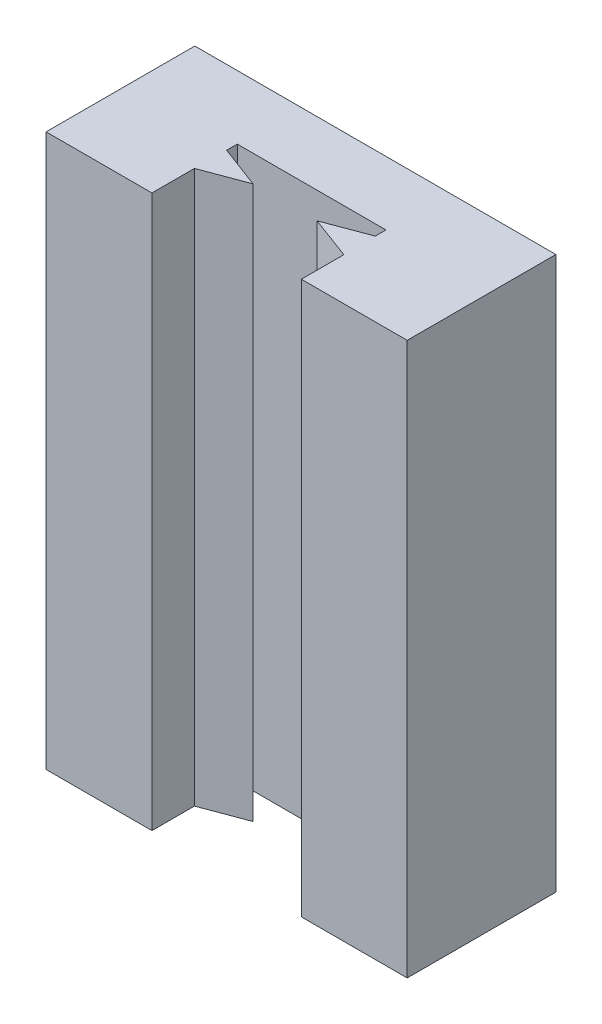
SolidWorks part; units mm, degrees
ref_plane "前视基准面" through (0, 0, 0) normal (0, 0, 1) x (1, 0, 0)
ref_plane "上视基准面" through (0, 0, 0) normal (0, 1, 0) x (1, 0, 0)
ref_plane "右视基准面" through (0, 0, 0) normal (1, 0, 0) x (0, 0, -1)
sketch "草图1" plane through (0, 0, 0) normal (0, 1, 0) x (1, 0, 0)
  line L0 (-96.3317, 0) -> (111.273, 0) construction
  line L1 (0, 100.067) -> (0, -107.1445) construction
  line L2 (-8.5, 0) -> (8.5, 0)
  line L3 (-8.5, 0) -> (-8.5, -7)
  line L4 (-8.5, -7) -> (-3.5176, -7)
  line L5 (-3.5176, -7) -> (-3.5176, -5)
  line L6 (-3.5176, -5) -> (-1.5086, -4.25)
  line L7 (-1.5086, -4.25) -> (-3.5, -3.5)
  line L8 (-3.5, -3.5) -> (-3.5, -3)
  line L9 (-3.5, -3) -> (3.5, -3)
  line L10 (-3.5, -3.5) -> (-3.5176, -5) construction
  line L11 (-3.5088, -4.25) -> (0.4915, -4.25) construction
  line L12 (3.5, -3.5) -> (3.5, -3)
  line L13 (1.5086, -4.25) -> (3.5, -3.5)
  line L14 (3.5176, -5) -> (1.5086, -4.25)
  line L15 (3.5176, -7) -> (3.5176, -5)
  line L16 (8.5, -7) -> (3.5176, -7)
  line L17 (8.5, 0) -> (8.5, -7)
  point P17 (0, -3)
  dimension "D1" = 17
  dimension "D2" = 3
  dimension "D3" = 7
  dimension "D4" = 1.5
  dimension "D5" = 2
  dimension "D6" = 2
  dimension "D7" = 7
  dimension "D8" = 1.25
extrude "凸台-拉伸1" add sketch "草图1" along normal blind 26
sketch "草图2" plane through (0, 0, 0) normal (0, 0, -1) x (-1, 0, 0)
  line L0 (0, 37.2649) -> (0, -13.776) construction
  circle A0 centre (6, 19.5) radius 1
  circle A1 centre (6, 6.5) radius 1
  circle A2 centre (-6, 6.5) radius 1
  circle A3 centre (-6, 19.5) radius 1
  dimension "D4" = 2
  dimension "D1" = 13
  dimension "D2" = 6
  dimension "D3" = 6.5
extrude "切除-拉伸1" cut sketch "草图2" against normal blind 3
cosmetic thread "装饰螺纹线1" parameters "D2"=3
cosmetic thread "装饰螺纹线2" parameters "D2"=3
cosmetic thread "装饰螺纹线3" parameters "D2"=3
cosmetic thread "装饰螺纹线4" parameters "D2"=3
